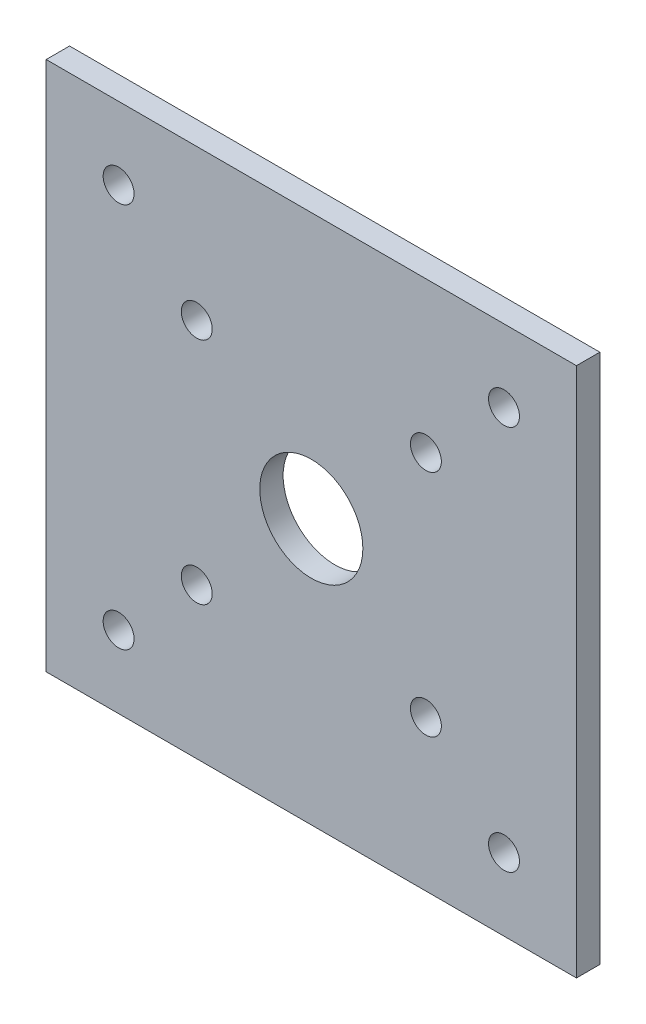
SolidWorks part; units mm, degrees
ref_plane "Front Plane" through (0, 0, 0) normal (0, 0, 1) x (1, 0, 0)
ref_plane "Top Plane" through (0, 0, 0) normal (0, 1, 0) x (1, 0, 0)
ref_plane "Right Plane" through (0, 0, 0) normal (1, 0, 0) x (0, 0, -1)
sketch "Sketch1" plane through (0, 0, 0) normal (0, 0, 1) x (1, 0, 0)
  line L0 (-15.5563, 15.5563) -> (0, 0) construction
  line L1 (-36, -36) -> (36, -36)
  line L2 (-36, -36) -> (-36, 36)
  line L3 (-36, 36) -> (36, 36)
  line L4 (36, -36) -> (36, 36)
  line L5 (-36, -36) -> (36, 36) construction
  line L6 (-36, 36) -> (36, -36) construction
  line L7 (0, 0) -> (-22, 0) construction
  circle A0 centre (0, 0) radius 22 construction
  circle A1 centre (-15.5563, 15.5563) radius 2.1
  circle A2 centre (15.5563, 15.5563) radius 2.1
  circle A3 centre (15.5563, -15.5563) radius 2.1
  circle A4 centre (-15.5563, -15.5563) radius 2.1
  circle A5 centre (0, 0) radius 37 construction
  circle A6 centre (26.163, 26.163) radius 2.1
  circle A7 centre (26.163, -26.163) radius 2.1
  circle A8 centre (-26.163, -26.163) radius 2.1
  circle A9 centre (-26.163, 26.163) radius 2.1
  circle A10 centre (0, 0) radius 7
  circle A11 centre (0, 0) radius 31.5 construction
  point P0 (0, 0)
  point P19 (0, 0)
  point P30 (0, 0)
  dimension "D2" = 44
  dimension "D3" = 4.2
  dimension "D6" = 74
  dimension "D7" = 4.2
  dimension "D9" = 14
  dimension "D10" = 63
  dimension "D1" = 72
  dimension "D5" = 45
  dimension "D4" = 4
  dimension "D8" = 4
extrude "Boss-Extrude1" add sketch "Sketch1" along normal mid plane 3.175 contours L1 L4 L3 L2 A9 A8 A7 A6 A4 A3 A2 A1
